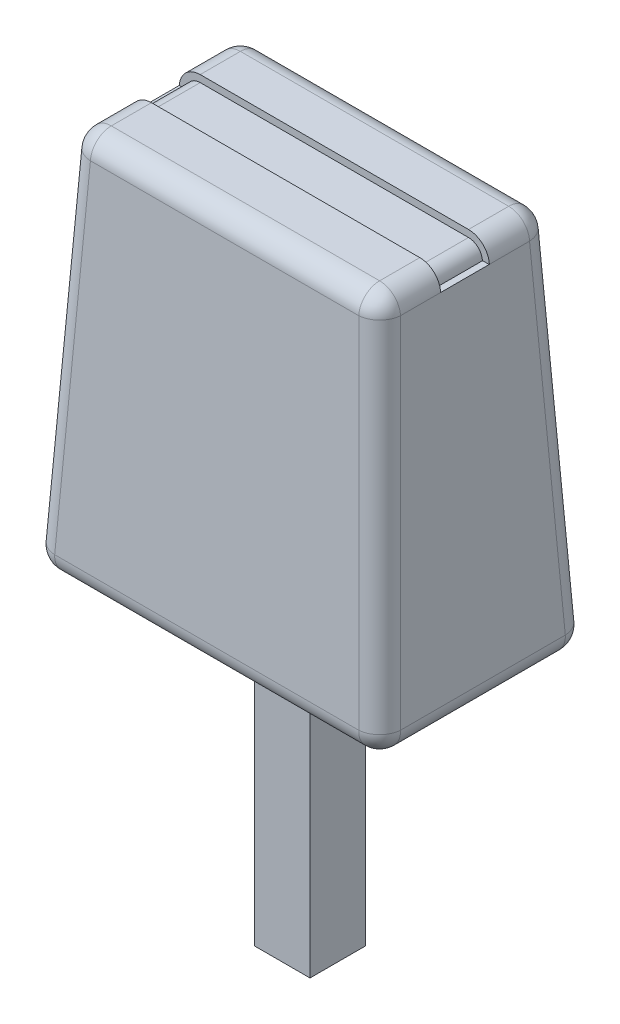
SolidWorks part; units mm, degrees
ref_plane "Front Plane" through (0, 0, 0) normal (0, 0, 1) x (1, 0, 0)
ref_plane "Top Plane" through (0, 0, 0) normal (0, 1, 0) x (1, 0, 0)
ref_plane "Right Plane" through (0, 0, 0) normal (1, 0, 0) x (0, 0, -1)
sketch "Sketch1" plane through (0, 0, 0) normal (0, 1, 0) x (1, 0, 0)
  line L1 (-12.5, -7.5) -> (12.5, -7.5)
  line L2 (-12.5, -7.5) -> (-12.5, 7.5)
  line L3 (-12.5, 7.5) -> (12.5, 7.5)
  line L4 (12.5, -7.5) -> (12.5, 7.5)
  line L5 (-12.5, -7.5) -> (12.5, 7.5) construction
  line L6 (-12.5, 7.5) -> (12.5, -7.5) construction
  point P0 (0, 0)
  dimension "D1" = 25
  dimension "D2" = 15
extrude "Boss-Extrude1" add sketch "Sketch1" along normal blind 27.5 draft 3
fillet "Fillet1" radius 1.5 12 edges at (0, 27.5, 6.0588) (-11.0588, 27.5, 0) (0, 27.5, -6.0588) (11.0588, 27.5, 0) (11.7794, 13.75, 6.7794) (11.7794, 13.75, -6.7794) (12.5, 0, 0) (-11.7794, 13.75, -6.7794) (-11.7794, 13.75, 6.7794) (-12.5, 0, 0) (0, 0, 7.5) (0, 0, -7.5)
sketch "Sketch2" plane through (0, 0, 0) normal (0, -1, 0) x (-1, 0, 0)
  line L1 (-2, -2) -> (2, -2)
  line L2 (-2, -2) -> (-2, 2)
  line L3 (-2, 2) -> (2, 2)
  line L4 (2, -2) -> (2, 2)
  line L5 (-2, -2) -> (2, 2) construction
  line L6 (-2, 2) -> (2, -2) construction
  point P0 (0, 0)
  dimension "D1" = 4
  dimension "D2" = 4
extrude "Boss-Extrude2" add sketch "Sketch2" along normal blind 21
sketch "Sketch3" plane through (0, 0, 0) normal (0, 0, 1) x (1, 0, 0)
  line L0 (-9.6353, 27.5) -> (9.6353, 27.5) construction
  line L1 (-9.6353, 27.5) -> (9.6353, 27.5)
  line L2 (-9.6353, 27) -> (9.6353, 27)
  line L3 (-11.1333, 26.0785) -> (-10.634, 26.0523)
  line L4 (10.634, 26.0523) -> (11.1333, 26.0785)
  arc A0 (11.1333, 26.0785) -> (9.6353, 27.5) centre (9.6353, 26) ccw construction
  arc A1 (-9.6353, 27.5) -> (-11.1333, 26.0785) centre (-9.6353, 26) ccw construction
  arc A2 (11.1333, 26.0785) -> (9.6353, 27.5) centre (9.6353, 26) ccw
  arc A3 (-9.6353, 27.5) -> (-11.1333, 26.0785) centre (-9.6353, 26) ccw
  arc A4 (-9.6353, 27) -> (-10.634, 26.0523) centre (-9.6353, 26) ccw
  arc A5 (10.634, 26.0523) -> (9.6353, 27) centre (9.6353, 26) ccw
  dimension "D1" = 0.5
extrude "Cut-Extrude1" cut sketch "Sketch3" against normal mid plane 3.5
